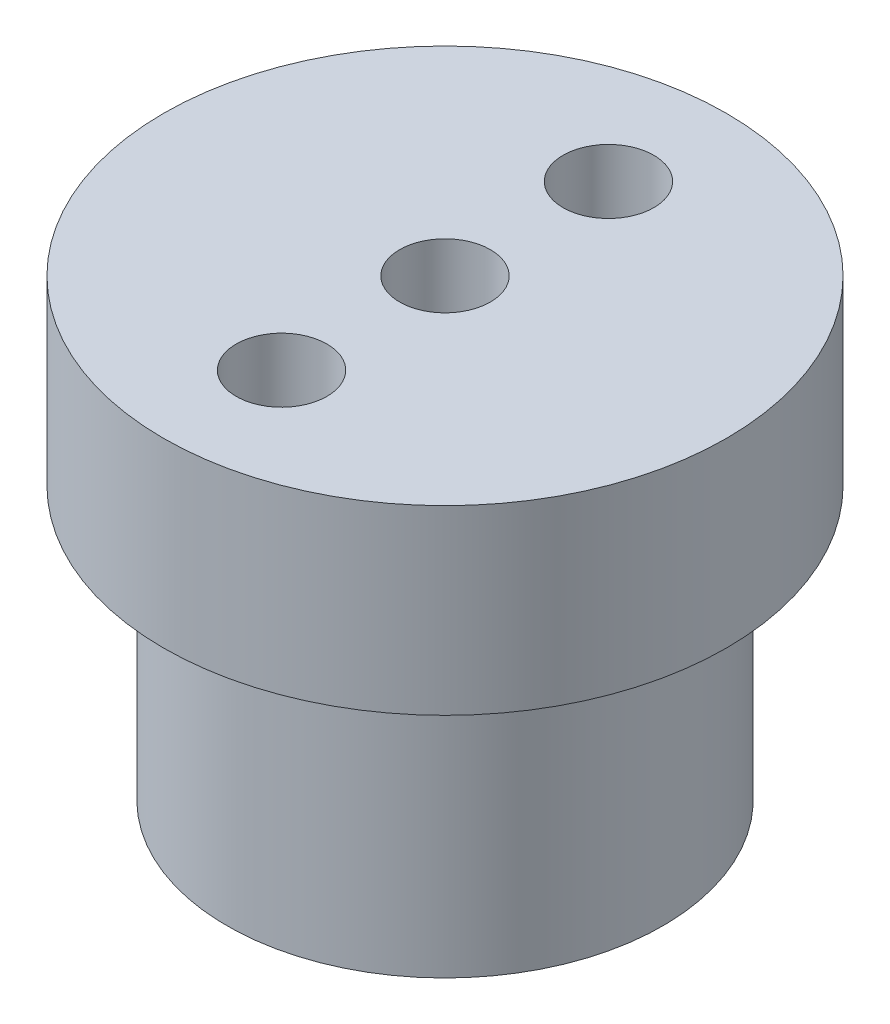
SolidWorks part; units mm, degrees
ref_plane "Front" through (0, 0, 0) normal (0, 0, 1) x (1, 0, 0)
ref_plane "Top" through (0, 0, 0) normal (0, 1, 0) x (1, 0, 0)
ref_plane "Right" through (0, 0, 0) normal (1, 0, 0) x (0, 0, -1)
sketch "Esquisse1" plane through (0, 0, 0) normal (0, 0, 1) x (1, 0, 0)
  line L2 (7.75, 12.5) -> (7.75, 7.5)
  line L3 (7.75, 7.5) -> (6, 7.5)
  line L4 (6, 7.5) -> (6, 0)
  line L5 (6, 0) -> (1.25, 0)
  line L6 (0, 0) -> (0, 12.5) construction
  line L7 (1.25, 0) -> (1.25, 12.5)
  line L8 (1.25, 12.5) -> (7.75, 12.5)
  point P6 (3.0602, 3.6034)
  point P9 (0, 3.6034)
  point P10 (0, 0)
  dimension "D1" = 7.5
  dimension "D2" = 5
  dimension "D3" = 12
  dimension "D4" = 15.5
  dimension "D5" = 1.75
  dimension "D6" = 2.5
revolve "Révolution1" add sketch "Esquisse1" angle 360 about L6
sketch "Esquisse2" plane through (0, 12.5, 0) normal (0, 1, 0) x (1, 0, 0)
  line L0 (-50, 0) -> (50, 0) construction
  circle A0 centre (0, 4.5) radius 1.25
  circle A1 centre (0, -4.5) radius 1.25
  circle A2 centre (0, 0) radius 1.25 construction
  point P6 (0, 0)
  dimension "D1" = 9
extrude "Enlèv. mat.-Extru.1" cut sketch "Esquisse2" against normal blind 10
